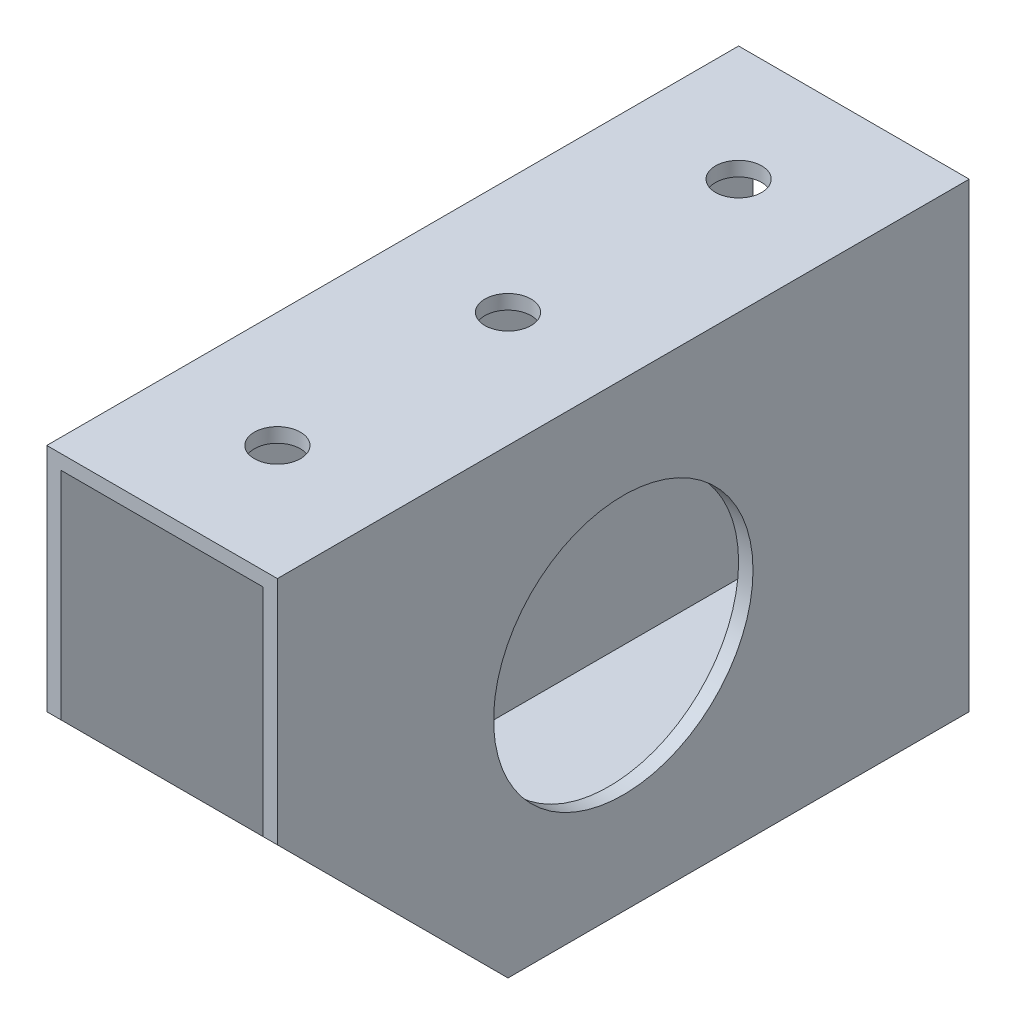
SolidWorks part; units mm, degrees
ref_plane "Front Plane" through (0, 0, 0) normal (0, 0, 1) x (1, 0, 0)
ref_plane "Top Plane" through (0, 0, 0) normal (0, 1, 0) x (1, 0, 0)
ref_plane "Right Plane" through (0, 0, 0) normal (1, 0, 0) x (0, 0, -1)
sketch "Sketch1" plane through (0, 0, 0) normal (0, 0, 1) x (1, 0, 0)
  line L1 (0, 0) -> (25.4, 0)
  line L2 (0, 0) -> (0, 50.8)
  line L3 (0, 50.8) -> (25.4, 50.8)
  line L4 (25.4, 0) -> (25.4, 50.8)
  line L5 (1.5875, 1.5875) -> (23.8125, 1.5875)
  line L6 (1.5875, 1.5875) -> (1.5875, 49.2125)
  line L7 (1.5875, 49.2125) -> (23.8125, 49.2125)
  line L8 (23.8125, 1.5875) -> (23.8125, 49.2125)
  dimension "D1" = 25.4
  dimension "D2" = 50.8
  dimension "D3" = 1.5875
  dimension "D4" = 1.5875
  dimension "D5" = 1.5875
  dimension ".0625" = 1.5875
extrude "Boss-Extrude1" add sketch "Sketch1" along normal blind 76.2
sketch "Sketch2" plane through (25.4, 0, 0) normal (1, 0, 0) x (0, 0, -1)
  line L3 (-76.2, 50.8) -> (0, 50.8) construction
  line L4 (0, 0) -> (0, 50.8) construction
  circle A43 centre (-38.1, 25.4) radius 14.2875
  dimension "D1" = 28.575
  dimension "D2" = 25.4
  dimension "1" = 38.1
extrude "Cut-Extrude1" cut sketch "Sketch2" against normal through all
sketch "Sketch3" plane through (25.4, 0, 0) normal (1, 0, 0) x (0, 0, -1)
  line L0 (-50.8, 0) -> (-76.2, 25.4)
  line L1 (-76.2, 0) -> (0, 0) construction
  line L2 (-76.2, 0) -> (-76.2, 50.8) construction
  line L3 (-76.2, 25.4) -> (-76.2, 0)
  line L4 (-76.2, 0) -> (-50.8, 0)
  dimension "D1" = 25.4
extrude "Cut-Extrude2" cut sketch "Sketch3" against normal through all
sketch "Sketch4" plane through (0, 50.8, 0) normal (0, 1, 0) x (1, 0, 0)
  line L0 (25.4, -76.2) -> (25.4, 0) construction
  line L1 (25.4, 0) -> (0, 0) construction
  circle A0 centre (12.7, -12.7) radius 2.54
  circle A1 centre (12.7, -38.1) radius 2.54
  circle A2 centre (12.7, -63.5) radius 2.54
  point P6 (0, 0)
  dimension "D1" = 5.08
  dimension "D2" = 12.7
  dimension "D3" = 12.7
  dimension "D4" = 25.4
  dimension "D5" = 25.4
extrude "Cut-Extrude3" cut sketch "Sketch4" against normal up to next
sketch "Sketch5" plane through (0, 0, 0) normal (0, -1, 0) x (1, 0, 0)
  line L0 (12.7, 50.8) -> (12.7, 0) construction
  line L1 (0, 50.8) -> (25.4, 50.8) construction
  line L2 (0, 0) -> (25.4, 0) construction
  circle A0 centre (12.7, 12.7) radius 2.54
  circle A1 centre (12.7, 39.6875) radius 2.54
  dimension "D3" = 5.08
  dimension "D1" = 12.7
  dimension "D2" = 26.9875
extrude "Cut-Extrude4" cut sketch "Sketch5" against normal up to next
